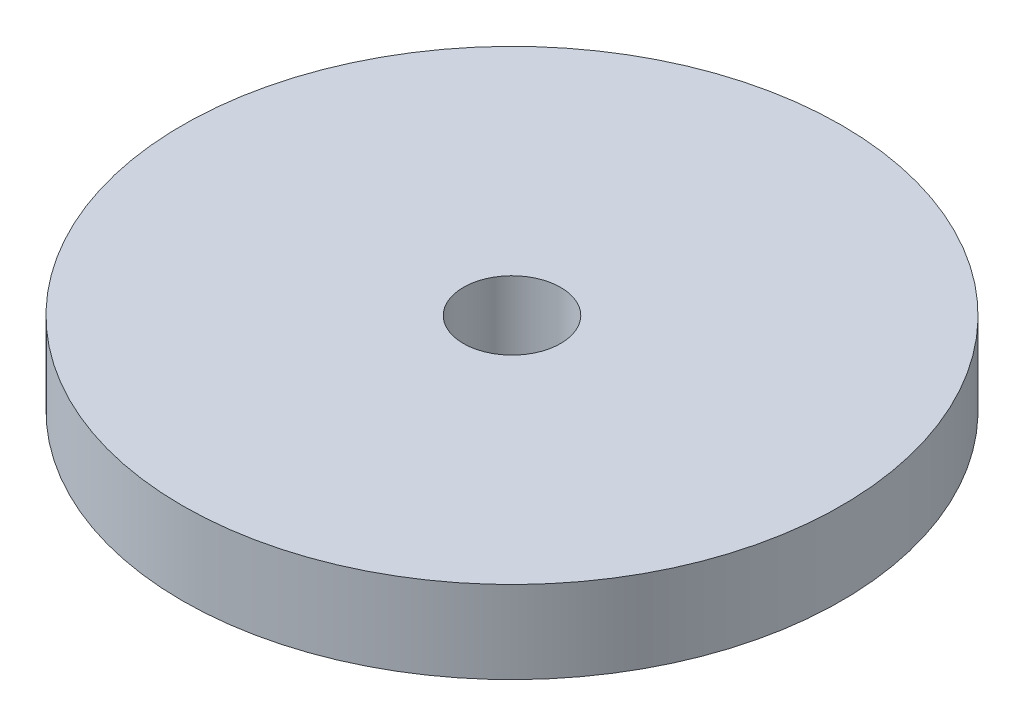
SolidWorks part; units mm, degrees
ref_plane "Front Plane" through (0, 0, 0) normal (0, 0, 1) x (1, 0, 0)
ref_plane "Top Plane" through (0, 0, 0) normal (0, 1, 0) x (1, 0, 0)
ref_plane "Right Plane" through (0, 0, 0) normal (1, 0, 0) x (0, 0, -1)
sketch "Sketch1" plane through (0, 0, 0) normal (0, 1, 0) x (1, 0, 0)
  circle A0 centre (0, 0) radius 1.5
  circle A1 centre (0, 0) radius 10.16
  dimension "D1" = 3
  dimension ".8" = 20.32
extrude "Boss-Extrude1" add sketch "Sketch1" along normal blind 2.54
